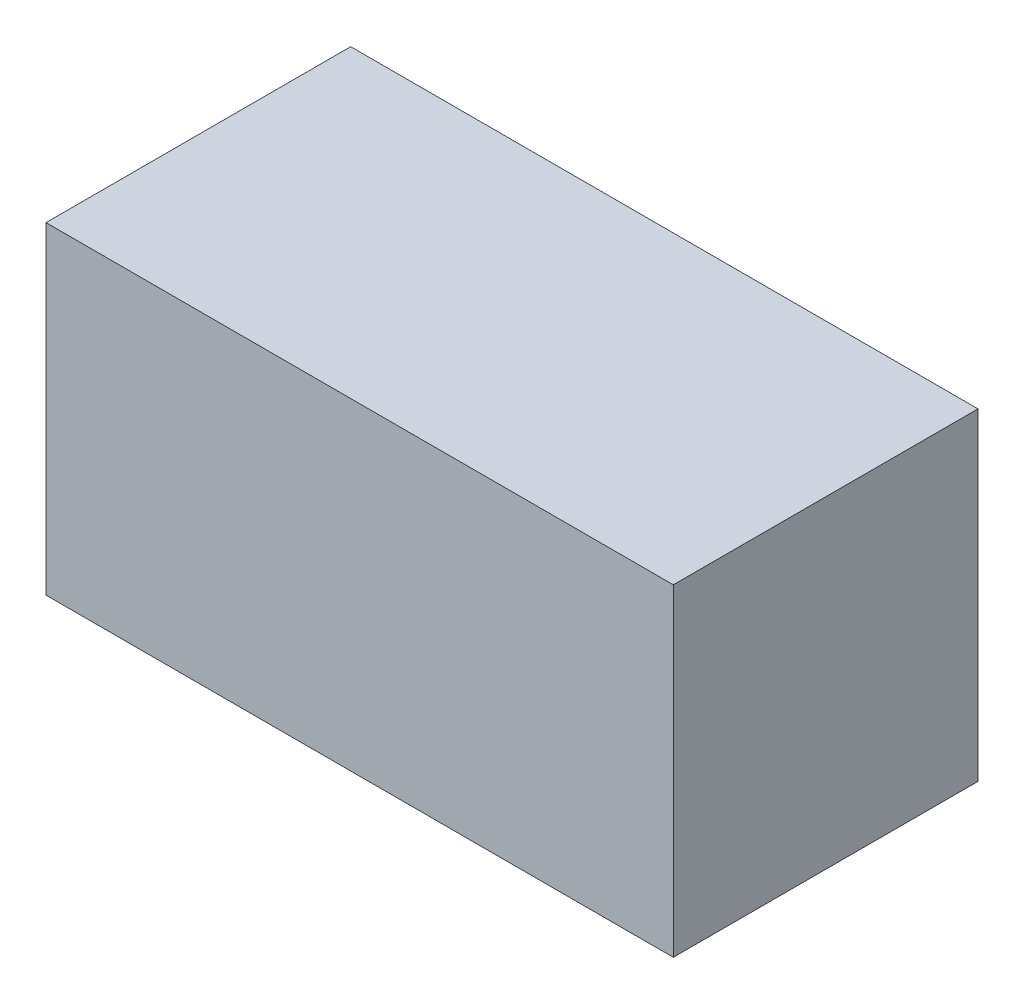
SolidWorks part; units mm, degrees
ref_plane "前视基准面" through (0, 0, 0) normal (0, 0, 1) x (1, 0, 0)
ref_plane "上视基准面" through (0, 0, 0) normal (0, 1, 0) x (1, 0, 0)
ref_plane "右视基准面" through (0, 0, 0) normal (1, 0, 0) x (0, 0, -1)
other "Configuration Table"
sketch "草图1" plane through (0, 0, 0) normal (0, 0, 1) x (1, 0, 0)
  line L1 (-35, -18) -> (35, -18)
  line L2 (-35, -18) -> (-35, 18)
  line L3 (-35, 18) -> (35, 18)
  line L4 (35, -18) -> (35, 18)
  line L5 (-35, -18) -> (35, 18) construction
  line L6 (-35, 18) -> (35, -18) construction
  point P0 (0, 0)
extrude "凸台-拉伸1" add sketch "草图1" along normal blind 34
